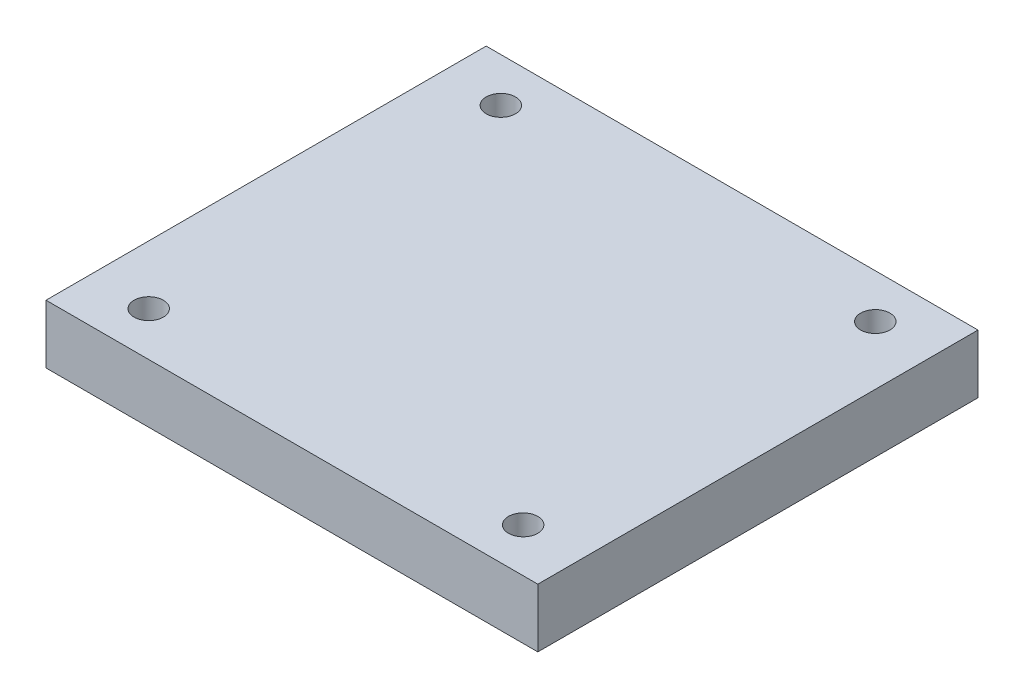
SolidWorks part; units mm, degrees
ref_plane "Front Plane" through (0, 0, 0) normal (0, 0, 1) x (1, 0, 0)
ref_plane "Top Plane" through (0, 0, 0) normal (0, 1, 0) x (1, 0, 0)
ref_plane "Right Plane" through (0, 0, 0) normal (1, 0, 0) x (0, 0, -1)
sketch "Sketch1" plane through (0, 0, 0) normal (0, 1, 0) x (1, 0, 0)
  line L0 (0, -91.2453) -> (0, 91.2453) construction
  line L1 (-53.213, 47.625) -> (53.213, 47.625)
  line L2 (-53.213, 47.625) -> (-53.213, -47.625)
  line L3 (-53.213, -47.625) -> (53.213, -47.625)
  line L4 (53.213, 47.625) -> (53.213, -47.625)
  line L5 (-53.213, 47.625) -> (53.213, -47.625) construction
  line L6 (-53.213, -47.625) -> (53.213, 47.625) construction
  line L7 (-94.0462, 0) -> (94.0462, 0) construction
  circle A0 centre (-40.513, 38.1) radius 3.175
  circle A1 centre (40.513, 38.1) radius 3.175
  circle A2 centre (40.513, -38.1) radius 3.175
  circle A3 centre (-40.513, -38.1) radius 3.175
  point P0 (0, 0)
  dimension "D5" = 6.35
  dimension "D1" = 106.426
  dimension "D2" = 95.25
  dimension "D3" = 9.525
  dimension "D4" = 12.7
extrude "Boss-Extrude1" add sketch "Sketch1" along normal blind 12.7
